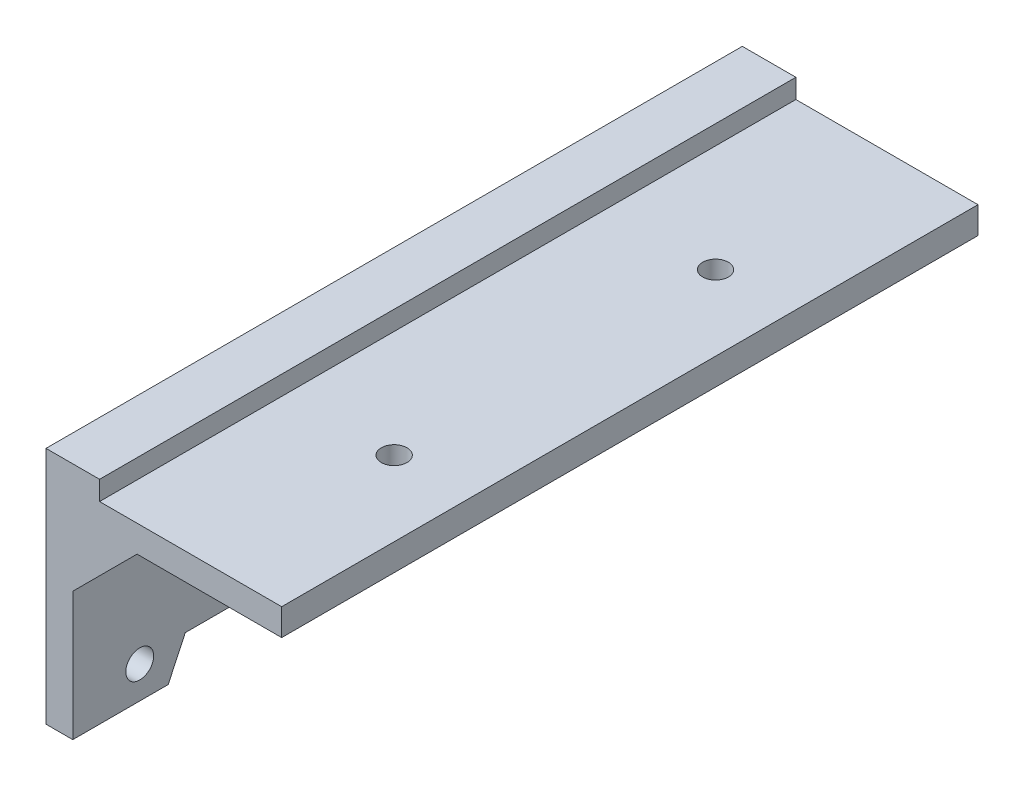
SolidWorks part; units mm, degrees
material "6061 Alloy"
ref_plane "Front Plane" through (0, 0, 0) normal (0, 0, 1) x (1, 0, 0)
ref_plane "Top Plane" through (0, 0, 0) normal (0, 1, 0) x (1, 0, 0)
ref_plane "Right Plane" through (0, 0, 0) normal (1, 0, 0) x (0, 0, -1)
sketch "Sketch1" plane through (0, 0, 0) normal (1, 0, 0) x (0, 0, -1)
  line L1 (-41.275, -13.335) -> (41.275, -13.335)
  line L2 (-41.275, -13.335) -> (-41.275, 13.335)
  line L3 (-41.275, 13.335) -> (41.275, 13.335)
  line L4 (41.275, -13.335) -> (41.275, 13.335)
  line L5 (0, 13.335) -> (0, -13.335) construction
  line L6 (-41.275, 0) -> (41.275, 0) construction
  point P0 (0, 0)
  dimension "D1" = 82.55
  dimension "D2" = 26.67
extrude "Boss-Extrude1" add sketch "Sketch1" along normal mid plane 3.175
sketch "Sketch2" plane through (-1.5875, 0, 0) normal (-1, 0, 0) x (0, 0, 1)
  line L0 (-33.3375, -5.715) -> (33.3375, -5.715) construction
  line L1 (41.275, -13.335) -> (-41.275, -13.335) construction
  line L2 (0, 13.335) -> (0, -13.335) construction
  line L3 (-41.275, 13.335) -> (41.275, 13.335) construction
  line L4 (-41.275, -13.335) -> (-41.275, 13.335) construction
  line L5 (41.275, 13.335) -> (41.275, -13.335) construction
  circle A0 centre (33.3375, -5.715) radius 1.651
  circle A1 centre (-33.3375, -5.715) radius 1.651
  circle A2 centre (-26.4795, -10.16) radius 1.5875
  circle A3 centre (26.4795, -10.16) radius 1.5875
  point P12 (0, -5.715)
  point P19 (0, -4.826)
  point P22 (0, -12.7)
  dimension "D1" = 66.675
  dimension "D2" = 7.9375
  dimension "D3" = 3.302
  dimension "D4" = 3.302
  dimension "D8" = 6.858
  dimension "D9" = 4.445
  dimension "D7" = 6.858
  dimension "D12" = 3.175
  dimension "D13" = 3.175
  dimension "D5" = 7.62
  dimension "D6" = 7.9375
  dimension "D10" = 7.62
  dimension "D11" = 4.445
extrude "Cut-Extrude1" cut sketch "Sketch2" against normal up to surface (3.175 mm away) up to face at (1.5875, 0, 0)
sketch "Sketch5" plane through (-1.5875, 0, 0) normal (-1, 0, 0) x (0, 0, 1)
  line L0 (0, 0) -> (0, 34.2734) construction
  line L3 (-41.275, 13.335) -> (41.275, 13.335) construction
  line L4 (-41.275, 16.51) -> (41.275, 16.51)
  line L5 (-41.275, 16.51) -> (-41.275, 13.335)
  line L6 (-41.275, 13.335) -> (41.275, 13.335)
  line L7 (41.275, 16.51) -> (41.275, 13.335)
  line L8 (0, 13.335) -> (0, 16.51) construction
  line L9 (-41.275, 14.9225) -> (41.275, 14.9225) construction
  point P2 (0, 14.9225)
  dimension "D1" = 3.175
  dimension "D2" = 82.55
extrude "Boss-Extrude3" add sketch "Sketch5" against normal blind 27.94
sketch "Sketch6" plane through (0, 16.51, 0) normal (0, 1, 0) x (1, 0, 0)
  line L0 (-1.5875, -41.275) -> (-1.5875, 41.275) construction
  line L1 (26.3525, -41.275) -> (-1.5875, -41.275) construction
  line L2 (26.3525, 41.275) -> (-1.5875, 41.275) construction
  circle A0 centre (17.4625, 19.05) radius 1.524
  circle A1 centre (17.4625, -19.05) radius 1.524
  dimension "D1" = 3.048
  dimension "D2" = 3.048
  dimension "D6" = 19.05
  dimension "D3" = 22.225
  dimension "D4" = 22.225
  dimension "D5" = 19.05
  dimension "D7" = 38.1
extrude "Cut-Extrude3" cut sketch "Sketch6" against normal up to surface (3.175 mm away) up to face at (13.97, 13.335, 0)
sketch "Sketch7" plane through (-1.5875, 0, 0) normal (-1, 0, 0) x (0, 0, 1)
  line L0 (0, 0) -> (0, -16.4603) construction
  line L1 (-31.75, -13.335) -> (31.75, -13.335)
  line L2 (41.275, -13.335) -> (-41.275, -13.335) construction
  line L3 (-27.94, -5.207) -> (27.94, -5.207)
  line L4 (-31.75, -13.335) -> (-27.94, -5.207)
  line L5 (27.94, -5.207) -> (31.75, -13.335)
  point P8 (0, -13.335)
  point P12 (0, -5.207)
  dimension "D1" = 63.5
  dimension "D2" = 55.88
  dimension "D3" = 3.81
  dimension "D4" = 3.81
  dimension "D5" = 8.128
extrude "Cut-Extrude4" cut sketch "Sketch7" against normal up to surface (3.175 mm away) up to face at (1.5875, -5.715, -31.6865)
sketch "Sketch8" plane through (0, 0, 41.275) normal (0, 0, 1) x (1, 0, 0)
  line L0 (1.5875, 13.335) -> (9.2075, 13.335)
  line L1 (26.3525, 13.335) -> (1.5875, 13.335) construction
  line L2 (1.5875, 5.715) -> (9.2075, 13.335)
  line L3 (1.5875, 13.335) -> (1.5875, -13.335) construction
  line L4 (1.5875, 5.715) -> (1.5875, 13.335)
  dimension "D1" = 7.62
  dimension "D2" = 7.62
extrude "Boss-Extrude4" add sketch "Sketch8" against normal up to surface (82.55 mm away) up to face at (8.7842, 5.5033, -41.275)
sketch "Sketch9" plane through (-1.5875, 0, 0) normal (-1, 0, 0) x (0, 0, 1)
  line L0 (-41.275, -13.335) -> (-41.275, -9.525)
  line L1 (-41.275, -13.335) -> (-41.275, 16.51) construction
  line L2 (-41.275, -9.525) -> (-29.9641, -9.525)
  line L3 (-27.94, -5.207) -> (-31.75, -13.335) construction
  line L4 (-29.9641, -9.525) -> (-31.75, -13.335)
  line L5 (-31.75, -13.335) -> (-41.275, -13.335)
  line L6 (41.275, -13.335) -> (41.275, -9.525)
  line L7 (41.275, 16.51) -> (41.275, -13.335) construction
  line L8 (41.275, -9.525) -> (29.9641, -9.525)
  line L9 (31.75, -13.335) -> (27.94, -5.207) construction
  line L10 (29.9641, -9.525) -> (31.75, -13.335)
  line L11 (31.75, -13.335) -> (41.275, -13.335)
  dimension "D1" = 3.81
  dimension "D2" = 3.81
extrude "Cut-Extrude5" cut sketch "Sketch9" against normal up to surface (3.175 mm away) up to face at (1.5875, -6.5405, 0)
sketch "Sketch10" plane through (0, 16.51, 0) normal (0, 1, 0) x (1, 0, 0)
  line L0 (26.3525, -41.275) -> (-1.5875, -41.275) construction
  line L1 (-1.5875, 41.275) -> (4.7625, 41.275)
  line L2 (-1.5875, 41.275) -> (-1.5875, -41.275)
  line L3 (-1.5875, -41.275) -> (4.7625, -41.275)
  line L4 (4.7625, 41.275) -> (4.7625, -41.275)
  dimension "D1" = 6.35
extrude "Boss-Extrude5" add sketch "Sketch10" along normal blind 2.286
